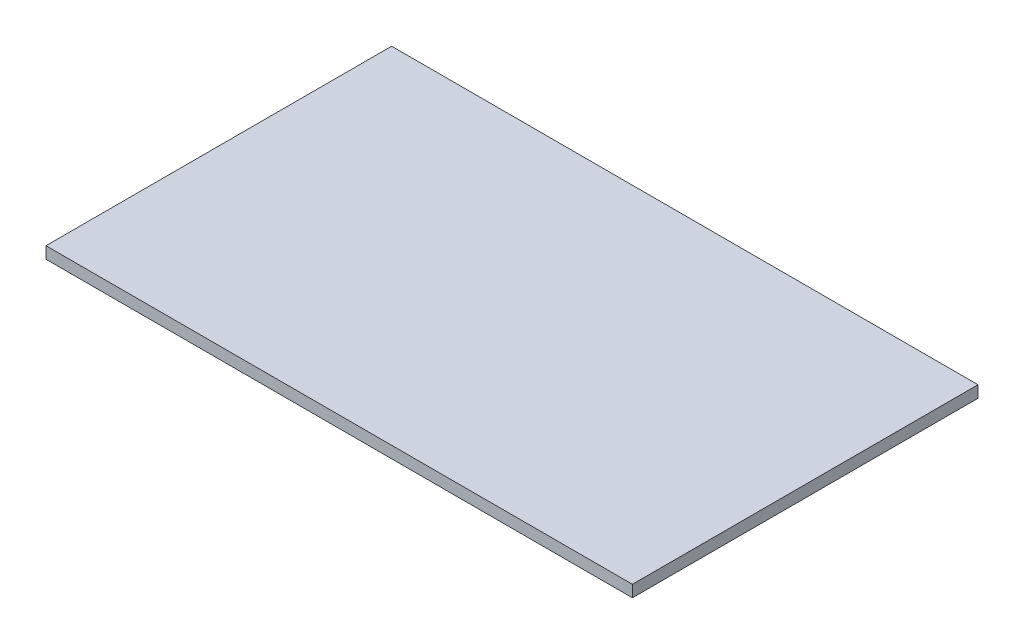
SolidWorks part; units mm, degrees
ref_plane "前视基准面" through (0, 0, 0) normal (0, 0, 1) x (1, 0, 0)
ref_plane "上视基准面" through (0, 0, 0) normal (0, 1, 0) x (1, 0, 0)
ref_plane "右视基准面" through (0, 0, 0) normal (1, 0, 0) x (0, 0, -1)
sketch "草图1" plane through (0, 0, 0) normal (0, 1, 0) x (1, 0, 0)
  line L1 (-2500, -1473.4347) -> (2500, -1473.4347)
  line L2 (-2500, -1473.4347) -> (-2500, 1473.4347)
  line L3 (-2500, 1473.4347) -> (2500, 1473.4347)
  line L4 (2500, -1473.4347) -> (2500, 1473.4347)
  line L5 (-2500, -1473.4347) -> (2500, 1473.4347) construction
  line L6 (-2500, 1473.4347) -> (2500, -1473.4347) construction
  point P0 (0, 0)
  dimension "D1" = 5000
extrude "凸台-拉伸1" add sketch "草图1" along normal blind 100
